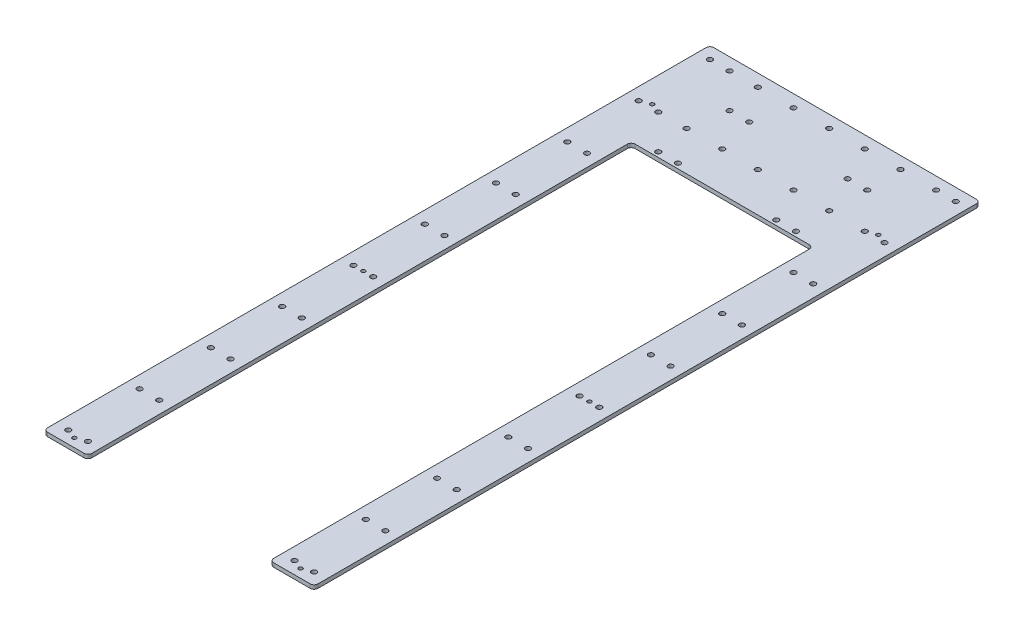
SolidWorks part; units mm, degrees
ref_plane "Front Plane" through (0, 0, 0) normal (0, 0, 1) x (1, 0, 0)
ref_plane "Top Plane" through (0, 0, 0) normal (0, 1, 0) x (1, 0, 0)
ref_plane "Right Plane" through (0, 0, 0) normal (1, 0, 0) x (0, 0, -1)
sketch "Sketch1" plane through (0, 0, 0) normal (0, 1, 0) x (1, 0, 0)
  line L0 (92, 271) -> (92, -271) construction
  line L1 (-110, -271) -> (-74, -271)
  line L2 (-110, -271) -> (-110, 271)
  line L3 (-110, 271) -> (110, 271)
  line L4 (110, -271) -> (110, 271)
  line L5 (-110, -271) -> (110, 271) construction
  line L6 (-110, 271) -> (110, -271) construction
  line L7 (100, 261) -> (100, 203) construction
  line L8 (0, 271) -> (0, -271) construction
  line L9 (-110, -29) -> (110, -29) construction
  line L10 (84, 261) -> (55, 261) construction
  line L11 (74, -271) -> (110, -271)
  line L13 (-74, -271) -> (-74, 171)
  line L14 (-74, 171) -> (74, 171)
  line L15 (74, -271) -> (74, 171)
  line L16 (-62.0332, 204) -> (-27.7286, 204) construction
  circle A0 centre (100, 261) radius 2.1
  circle A1 centre (100, 203) radius 2.1
  circle A2 centre (100, 145) radius 2.1
  circle A3 centre (100, 87) radius 2.1
  circle A4 centre (100, 29) radius 2.1
  circle A5 centre (100, -29) radius 2.1
  circle A6 centre (100, -87) radius 2.1
  circle A7 centre (100, -145) radius 2.1
  circle A8 centre (100, -203) radius 2.1
  circle A9 centre (100, -261) radius 2.1
  circle A10 centre (84, -261) radius 2.1
  circle A11 centre (84, -203) radius 2.1
  circle A12 centre (84, -145) radius 2.1
  circle A13 centre (84, -87) radius 2.1
  circle A14 centre (84, -29) radius 2.1
  circle A15 centre (84, 29) radius 2.1
  circle A16 centre (84, 87) radius 2.1
  circle A17 centre (84, 145) radius 2.1
  circle A18 centre (84, 203) radius 2.1
  circle A19 centre (84, 261) radius 2.1
  circle A20 centre (92, -29) radius 1.6
  circle A21 centre (92, 206) radius 1.6
  circle A22 centre (92, -264) radius 1.6
  circle A23 centre (-100, 261) radius 2.1
  circle A24 centre (-84, 261) radius 2.1
  circle A25 centre (-92, 206) radius 1.6
  circle A26 centre (-84, 87) radius 2.1
  circle A27 centre (-100, 87) radius 2.1
  circle A28 centre (-100, 145) radius 2.1
  circle A29 centre (-100, 203) radius 2.1
  circle A30 centre (-92, -264) radius 1.6
  circle A31 centre (-92, -29) radius 1.6
  circle A32 centre (-84, 29) radius 2.1
  circle A33 centre (-84, -29) radius 2.1
  circle A34 centre (-84, -87) radius 2.1
  circle A35 centre (-84, -145) radius 2.1
  circle A36 centre (-84, -203) radius 2.1
  circle A37 centre (-84, -261) radius 2.1
  circle A38 centre (-100, -261) radius 2.1
  circle A39 centre (-100, -203) radius 2.1
  circle A40 centre (-100, -145) radius 2.1
  circle A41 centre (-100, -87) radius 2.1
  circle A42 centre (-100, -29) radius 2.1
  circle A43 centre (-100, 29) radius 2.1
  circle A44 centre (-84, 203) radius 2.1
  circle A45 centre (-84, 145) radius 2.1
  circle A46 centre (55, 261) radius 2.1
  circle A47 centre (26, 261) radius 2.1
  circle A48 centre (-3, 261) radius 2.1
  circle A49 centre (-32, 261) radius 2.1
  circle A50 centre (-61, 261) radius 2.1
  circle A51 centre (55, 203) radius 2.1
  circle A52 centre (26, 203) radius 2.1
  circle A53 centre (-3, 203) radius 2.1
  circle A54 centre (-32, 203) radius 2.1
  circle A55 centre (-61, 203) radius 2.1
  circle A56 centre (84, 203) radius 2.1
  circle A57 centre (-56, 175) radius 2.1
  circle A58 centre (-40, 175) radius 2.1
  circle A59 centre (-40, 233) radius 2.1
  circle A60 centre (-56, 233) radius 2.1
  circle A61 centre (40, 175) radius 2.1
  circle A62 centre (56, 175) radius 2.1
  circle A63 centre (56, 233) radius 2.1
  circle A64 centre (40, 233) radius 2.1
  point P0 (0, 0)
  dimension "D4" = 4.2
  dimension "D10" = 3.2
  dimension "D11" = 3.2
  dimension "D21" = 4.2
  dimension "D22" = 4.2
  dimension "D1" = 220
  dimension "D2" = 542
  dimension "D3" = 18
  dimension "D5" = 10
  dimension "D6" = 8
  dimension "D8" = 58
  dimension "D9" = 300
  dimension "D12" = 235
  dimension "D15" = 29
  dimension "D16" = 10
  dimension "D17" = 10
  dimension "D18" = 100
  dimension "D19" = 4
  dimension "D20" = 18
  dimension "D23" = 16
  dimension "D24" = 29
  dimension "D7" = 10
  dimension "D13" = 6
  dimension "D14" = 2
extrude "Boss-Extrude1" add sketch "Sketch1" along normal blind 3.175 contours L15 L11 L4 L3 L2 L1 L13 L14 A54 A52 A50 A48 A46 A45 A44 A42 A40 A38 A37 A36 A35 A34 A33 A32 A29 A27 A26 A23 A19
fillet "Fillet1" radius 3.2 8 edges at (-110, 1.5875, -271) (110, 1.5875, -271) (74, 1.5875, -171) (-74, 1.5875, -171) (110, 1.5875, 271) (74, 1.5875, 271) (-110, 1.5875, 271) (-74, 1.5875, 271)
equation "\"m3\"= 3.2"
equation "\"m4\"= 4.2"
equation "\"width\"= 220"
equation "\"height\"= 600 - ( 58 / 2 ) - 29"
equation "\"D1@Sketch1\"=\"width\""
equation "\"D2@Sketch1\"=\"height\""
equation "\"D4@Sketch1\"=\"m4\""
equation "\"D10@Sketch1\"=\"m3\""
equation "\"D11@Sketch1\"=\"m3\""
equation "\"D21@Sketch1\"=\"m4\""
equation "\"D22@Sketch1\"=\"m4\""
